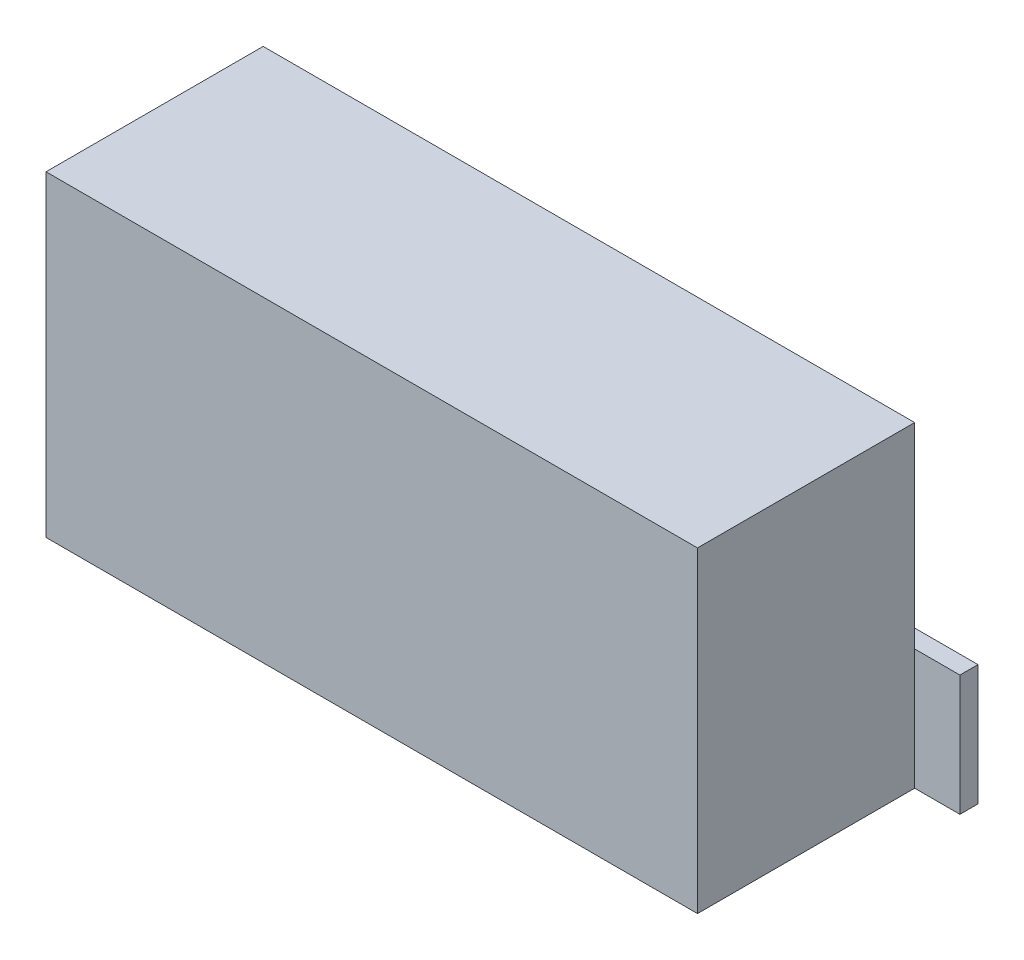
SolidWorks part; units mm, degrees
ref_plane "前视基准面" through (0, 0, 0) normal (0, 0, 1) x (1, 0, 0)
ref_plane "上视基准面" through (0, 0, 0) normal (0, 1, 0) x (1, 0, 0)
ref_plane "右视基准面" through (0, 0, 0) normal (1, 0, 0) x (0, 0, -1)
sketch "草图1" plane through (0, 0, 0) normal (0, 1, 0) x (1, 0, 0)
  line L1 (-54, 18) -> (54, 18)
  line L2 (-54, 18) -> (-54, -18)
  line L3 (-54, -18) -> (54, -18)
  line L4 (54, 18) -> (54, -18)
  line L5 (-54, 18) -> (54, -18) construction
  line L6 (-54, -18) -> (54, 18) construction
  point P0 (0, 0)
  dimension "D1" = 108
  dimension "D2" = 36
extrude "凸台-拉伸1" add sketch "草图1" along normal blind 52.5
ref_plane "基准面1" through (0, 0, -18) normal (0, 0, -1) x (-1, 0, 0)
sketch "草图2" plane through (0, 0, -18) normal (0, 0, -1) x (-1, 0, 0)
  line L0 (-54, 52.5) -> (-54, 0) construction
  line L1 (-61.5, 20) -> (-46.5, 20)
  line L2 (-61.5, 20) -> (-61.5, 0)
  line L3 (-61.5, 0) -> (-46.5, 0)
  line L4 (-46.5, 20) -> (-46.5, 0)
  line L5 (-61.5, 20) -> (-46.5, 0) construction
  line L6 (-61.5, 0) -> (-46.5, 20) construction
  line L7 (-54, 0) -> (54, 0) construction
  point P0 (-54, 10)
  dimension "D1" = 20
  dimension "D2" = 15
extrude "凸台-拉伸2" add sketch "草图2" along normal blind 3
